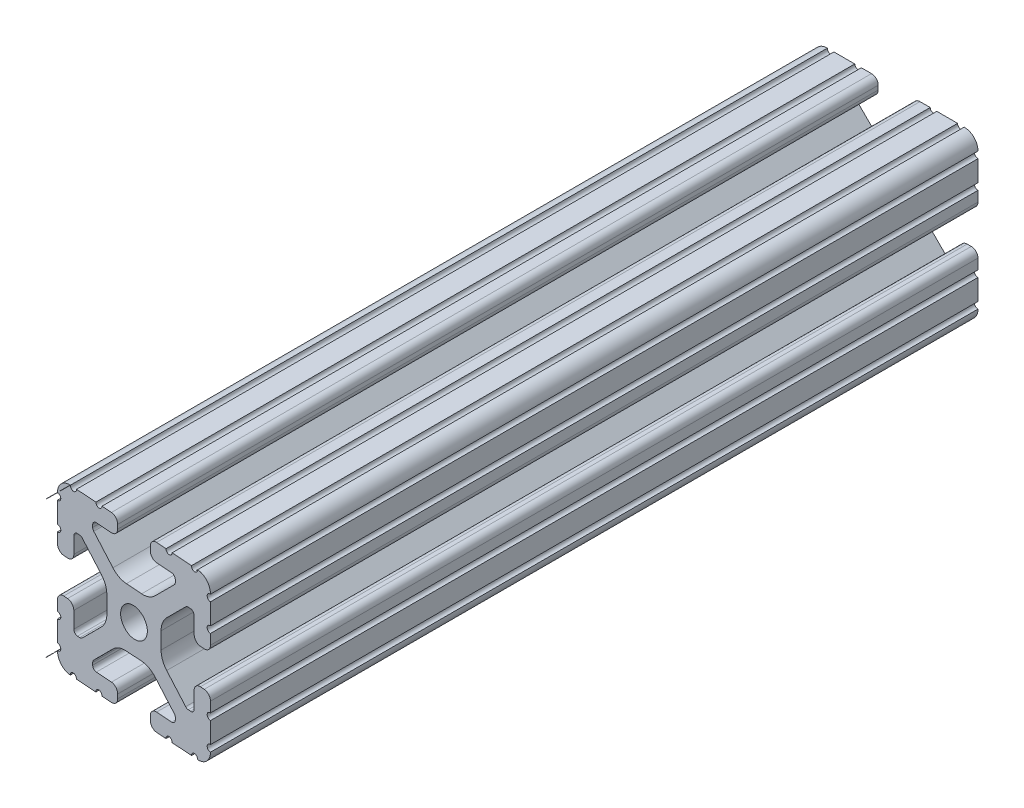
SolidWorks part; units mm, degrees
material "6061 Alloy"
ref_plane "Front Plane" through (0, 0, 0) normal (0, 0, 1) x (1, 0, 0)
ref_plane "Top Plane" through (0, 0, 0) normal (0, 1, 0) x (1, 0, 0)
ref_plane "Right Plane" through (0, 0, 0) normal (1, 0, 0) x (0, 0, -1)
sketch "Sketch1" plane through (0, 0, 0) normal (0, 0, 1) x (1, 0, 0)
  line L0 (0, 25.6181) -> (0, -24.623) construction
  line L1 (-20.8943, 0) -> (20.4607, 0) construction
  line L2 (-10.0229, 12.9148) -> (-5.2522, 8.144)
  line L3 (-10.287, 14.0843) -> (-10.287, 13.5524)
  line L4 (-5.6176, 14.986) -> (-9.3853, 14.986)
  line L5 (-4.064, 17.4964) -> (-4.064, 16.5396)
  line L6 (-7.9742, 19.05) -> (-5.6176, 19.05)
  line L7 (-14.3277, 19.05) -> (-9.4982, 19.05)
  line L8 (-19.05, 9.4961) -> (-19.05, 14.3277)
  line L9 (-19.05, 5.6176) -> (-19.05, 7.9763)
  line L10 (-16.5396, 4.064) -> (-17.4964, 4.064)
  line L11 (-14.986, 9.3853) -> (-14.986, 5.6176)
  line L12 (-13.516, 10.287) -> (-14.0843, 10.287)
  line L13 (-8.1476, 5.2921) -> (-12.8784, 10.0229)
  line L14 (-6.7564, -1.9335) -> (-6.7564, 1.9335)
  line L15 (-12.8784, -10.0229) -> (-8.1476, -5.2921)
  line L16 (-14.0843, -10.287) -> (-13.516, -10.287)
  line L17 (-14.986, -5.6176) -> (-14.986, -9.3853)
  line L18 (-17.4964, -4.064) -> (-16.5396, -4.064)
  line L19 (-19.05, -7.9763) -> (-19.05, -5.6176)
  line L20 (-19.05, -14.3277) -> (-19.05, -9.4961)
  line L21 (-9.4961, -19.05) -> (-14.3277, -19.05)
  line L22 (-5.6176, -19.05) -> (-7.9763, -19.05)
  line L23 (-4.064, -17.4964) -> (-4.064, -16.5396)
  line L24 (10.0229, -12.9148) -> (5.2522, -8.144)
  line L25 (10.287, -14.0843) -> (10.287, -13.5524)
  line L26 (5.6176, -14.986) -> (9.3853, -14.986)
  line L28 (-1.9022, 6.7564) -> (1.9022, 6.7564)
  line L29 (-1.9022, -6.7564) -> (1.9022, -6.7564)
  line L31 (-5.6176, -14.986) -> (-9.3853, -14.986)
  line L32 (-10.287, -14.0843) -> (-10.287, -13.5524)
  line L33 (-10.0229, -12.9148) -> (-5.2522, -8.144)
  line L66 (4.064, -16.5396) -> (4.064, -17.4964)
  line L67 (5.6176, -19.05) -> (7.9763, -19.05)
  line L68 (9.4961, -19.05) -> (14.3277, -19.05)
  line L69 (19.05, -14.3277) -> (19.05, -9.4961)
  line L70 (19.05, -7.9763) -> (19.05, -5.6176)
  line L71 (17.4964, -4.064) -> (16.5396, -4.064)
  line L72 (14.986, -5.6176) -> (14.986, -9.3853)
  line L73 (14.0843, -10.287) -> (13.516, -10.287)
  line L74 (12.8784, -10.0229) -> (8.1476, -5.2921)
  line L75 (6.7564, -1.9335) -> (6.7564, 1.9335)
  line L76 (8.1476, 5.2921) -> (12.8784, 10.0229)
  line L77 (13.516, 10.287) -> (14.0843, 10.287)
  line L78 (14.986, 9.3853) -> (14.986, 5.6176)
  line L79 (16.5396, 4.064) -> (17.4964, 4.064)
  line L80 (19.05, 5.6176) -> (19.05, 7.9763)
  line L81 (19.05, 9.4961) -> (19.05, 14.3277)
  line L82 (14.3277, 19.05) -> (9.4982, 19.05)
  line L83 (7.9742, 19.05) -> (5.6176, 19.05)
  line L84 (4.064, 17.4964) -> (4.064, 16.5396)
  line L85 (5.6176, 14.986) -> (9.3853, 14.986)
  line L86 (10.287, 14.0843) -> (10.287, 13.5524)
  line L87 (10.0229, 12.9148) -> (5.2522, 8.144)
  arc A0 (-10.0229, 12.9148) -> (-10.287, 13.5524) centre (-9.3853, 13.5524) cw
  circle A1 centre (0, 0) radius 3.3274
  arc A2 (-10.287, 14.0843) -> (-9.3853, 14.986) centre (-9.3853, 14.0843) cw
  arc A3 (-4.064, 16.5396) -> (-5.6176, 14.986) centre (-5.6176, 16.5396) cw
  arc A4 (-5.6176, 19.05) -> (-4.064, 17.4964) centre (-5.6176, 17.4964) cw
  arc A5 (-7.9742, 19.05) -> (-9.4982, 19.05) centre (-8.7362, 19.05) cw
  arc A6 (-14.3277, 19.05) -> (-15.8475, 19.05) centre (-15.0876, 18.9933) cw
  arc A7 (-19.05, 15.8475) -> (-15.8475, 19.05) centre (-15.8751, 15.8751) cw
  arc A8 (-19.05, 15.8475) -> (-19.05, 14.3277) centre (-18.9933, 15.0876) cw
  arc A9 (-19.05, 9.4961) -> (-19.05, 7.9763) centre (-18.9933, 8.7362) cw
  arc A10 (-17.4964, 4.064) -> (-19.05, 5.6176) centre (-17.4964, 5.6176) cw
  arc A11 (-14.986, 5.6176) -> (-16.5396, 4.064) centre (-16.5396, 5.6176) cw
  arc A12 (-14.986, 9.3853) -> (-14.0843, 10.287) centre (-14.0843, 9.3853) cw
  arc A13 (-13.516, 10.287) -> (-12.8784, 10.0229) centre (-13.516, 9.3853) cw
  arc A14 (-8.1476, 5.2921) -> (-6.7564, 1.9335) centre (-11.5062, 1.9335) cw
  arc A15 (-6.7564, -1.9335) -> (-8.1476, -5.2921) centre (-11.5062, -1.9335) cw
  arc A16 (-12.8784, -10.0229) -> (-13.516, -10.287) centre (-13.516, -9.3853) cw
  arc A17 (-14.0843, -10.287) -> (-14.986, -9.3853) centre (-14.0843, -9.3853) cw
  arc A18 (-16.5396, -4.064) -> (-14.986, -5.6176) centre (-16.5396, -5.6176) cw
  arc A19 (-19.05, -5.6176) -> (-17.4964, -4.064) centre (-17.4964, -5.6176) cw
  arc A20 (-19.05, -7.9763) -> (-19.05, -9.4961) centre (-18.9933, -8.7362) cw
  arc A21 (-19.05, -14.3277) -> (-19.05, -15.8475) centre (-18.9933, -15.0876) cw
  arc A22 (-15.8475, -19.05) -> (-19.05, -15.8475) centre (-15.8751, -15.8751) cw
  arc A23 (-15.8475, -19.05) -> (-14.3277, -19.05) centre (-15.0876, -18.9933) cw
  arc A24 (-9.4961, -19.05) -> (-7.9763, -19.05) centre (-8.7362, -18.9933) cw
  arc A25 (-4.064, -17.4964) -> (-5.6176, -19.05) centre (-5.6176, -17.4964) cw
  arc A26 (-5.2522, -8.144) -> (-1.9022, -6.7564) centre (-1.9022, -11.494) cw
  arc A27 (1.9022, -6.7564) -> (5.2522, -8.144) centre (1.9022, -11.494) cw
  arc A28 (10.0229, -12.9148) -> (10.287, -13.5524) centre (9.3853, -13.5524) cw
  arc A29 (10.287, -14.0843) -> (9.3853, -14.986) centre (9.3853, -14.0843) cw
  arc A30 (4.064, -16.5396) -> (5.6176, -14.986) centre (5.6176, -16.5396) cw
  arc A31 (-4.064, -16.5396) -> (-5.6176, -14.986) centre (-5.6176, -16.5396) ccw
  arc A32 (-10.287, -14.0843) -> (-9.3853, -14.986) centre (-9.3853, -14.0843) ccw
  arc A33 (-10.0229, -12.9148) -> (-10.287, -13.5524) centre (-9.3853, -13.5524) ccw
  arc A79 (4.064, -17.4964) -> (5.6176, -19.05) centre (5.6176, -17.4964) ccw
  arc A80 (9.4961, -19.05) -> (7.9763, -19.05) centre (8.7362, -18.9933) ccw
  arc A81 (15.8475, -19.05) -> (14.3277, -19.05) centre (15.0876, -18.9933) ccw
  arc A82 (15.8475, -19.05) -> (19.05, -15.8475) centre (15.8751, -15.8751) ccw
  arc A83 (19.05, -14.3277) -> (19.05, -15.8475) centre (18.9933, -15.0876) ccw
  arc A84 (19.05, -7.9763) -> (19.05, -9.4961) centre (18.9933, -8.7362) ccw
  arc A85 (19.05, -5.6176) -> (17.4964, -4.064) centre (17.4964, -5.6176) ccw
  arc A86 (16.5396, -4.064) -> (14.986, -5.6176) centre (16.5396, -5.6176) ccw
  arc A87 (14.0843, -10.287) -> (14.986, -9.3853) centre (14.0843, -9.3853) ccw
  arc A88 (12.8784, -10.0229) -> (13.516, -10.287) centre (13.516, -9.3853) ccw
  arc A89 (6.7564, -1.9335) -> (8.1476, -5.2921) centre (11.5062, -1.9335) ccw
  arc A90 (8.1476, 5.2921) -> (6.7564, 1.9335) centre (11.5062, 1.9335) ccw
  arc A91 (13.516, 10.287) -> (12.8784, 10.0229) centre (13.516, 9.3853) ccw
  arc A92 (14.986, 9.3853) -> (14.0843, 10.287) centre (14.0843, 9.3853) ccw
  arc A93 (14.986, 5.6176) -> (16.5396, 4.064) centre (16.5396, 5.6176) ccw
  arc A94 (17.4964, 4.064) -> (19.05, 5.6176) centre (17.4964, 5.6176) ccw
  arc A95 (19.05, 9.4961) -> (19.05, 7.9763) centre (18.9933, 8.7362) ccw
  arc A96 (19.05, 15.8475) -> (19.05, 14.3277) centre (18.9933, 15.0876) ccw
  arc A97 (19.05, 15.8475) -> (15.8475, 19.05) centre (15.8751, 15.8751) ccw
  arc A98 (14.3277, 19.05) -> (15.8475, 19.05) centre (15.0876, 18.9933) ccw
  arc A99 (7.9742, 19.05) -> (9.4982, 19.05) centre (8.7362, 19.05) ccw
  arc A100 (5.6176, 19.05) -> (4.064, 17.4964) centre (5.6176, 17.4964) ccw
  arc A101 (4.064, 16.5396) -> (5.6176, 14.986) centre (5.6176, 16.5396) ccw
  arc A102 (10.287, 14.0843) -> (9.3853, 14.986) centre (9.3853, 14.0843) ccw
  arc A103 (10.0229, 12.9148) -> (10.287, 13.5524) centre (9.3853, 13.5524) ccw
  arc A104 (1.9022, 6.7564) -> (5.2522, 8.144) centre (1.9022, 11.494) ccw
  arc A105 (-5.2522, 8.144) -> (-1.9022, 6.7564) centre (-1.9022, 11.494) ccw
  dimension "D1" = 6.6548
  dimension "D2" = 19.05
  dimension "D3" = 38.1
  dimension "D4" = 20.574
  dimension "D5" = 13.5128
  dimension "D6" = 4.064
  dimension "D7" = 8.128
  dimension "D8" = 4.064
  dimension "D9" = 12.2936
extrude "Extrude1" add sketch "Sketch1" against normal blind 177.8
sketch "Sketch2" plane through (0, 19.05, 0) normal (0, 1, 0) x (1, 0, 0)
  line L0 (19.05, 0) -> (-19.05, 2.6642)
  line L1 (-19.05, 177.8) -> (-19.05, 0) construction
  line L2 (-19.05, 2.6642) -> (-19.05, 0)
  line L3 (-19.05, 0) -> (19.05, 0)
  dimension "D1" = 4
extrude "Cut-Extrude1" cut sketch "Sketch2" against normal through all
